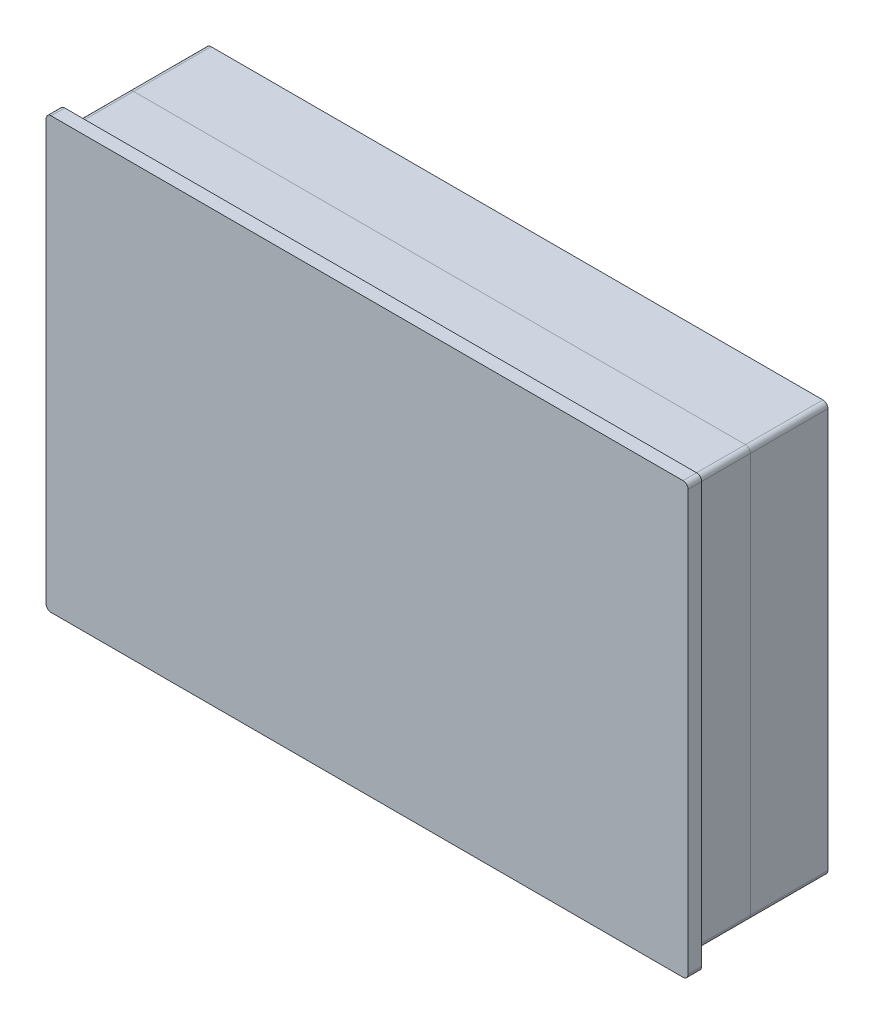
SolidWorks part; units mm, degrees
ref_plane "Front Plane" through (0, 0, 0) normal (0, 0, 1) x (1, 0, 0)
ref_plane "Top Plane" through (0, 0, 0) normal (0, 1, 0) x (1, 0, 0)
ref_plane "Right Plane" through (0, 0, 0) normal (1, 0, 0) x (0, 0, -1)
sketch "Sketch1" plane through (0, 0, 0) normal (0, 0, 1) x (1, 0, 0)
  line L1 (-140.9464, -80.3248) -> (-13.3464, -80.3248)
  line L2 (-140.9464, -80.3248) -> (-140.9464, -165.8248)
  line L3 (-140.9464, -165.8248) -> (-13.3464, -165.8248)
  line L4 (-13.3464, -80.3248) -> (-13.3464, -165.8248)
  line L5 (-140.9464, -80.3248) -> (-13.3464, -165.8248) construction
  line L6 (-140.9464, -165.8248) -> (-13.3464, -80.3248) construction
  point P0 (-77.1464, -123.0748)
  dimension "D1" = 127.6
  dimension "D2" = 85.5
extrude "Boss-Extrude1" add sketch "Sketch1" along normal blind 14.4
sketch "Sketch2" plane through (0, 0, 0) normal (0, 0, -1) x (-1, 0, 0)
  line L8 (15.3464, -82.3248) -> (15.3464, -163.8248)
  line L9 (15.3464, -163.8248) -> (138.9464, -163.8248)
  line L10 (138.9464, -163.8248) -> (138.9464, -82.3248)
  line L11 (138.9464, -82.3248) -> (15.3464, -82.3248)
  line L12 (15.3464, -82.3248) -> (15.3464, -163.8248)
  line L13 (15.3464, -163.8248) -> (138.9464, -163.8248)
  line L14 (138.9464, -163.8248) -> (138.9464, -82.3248)
  line L15 (138.9464, -82.3248) -> (15.3464, -82.3248)
  line L16 (13.3464, -80.3248) -> (13.3464, -165.8248)
  line L17 (13.3464, -165.8248) -> (140.9464, -165.8248)
  line L18 (140.9464, -165.8248) -> (140.9464, -80.3248)
  line L19 (140.9464, -80.3248) -> (13.3464, -80.3248)
  line L20 (13.3464, -80.3248) -> (13.3464, -165.8248)
  line L21 (13.3464, -165.8248) -> (140.9464, -165.8248)
  line L22 (140.9464, -165.8248) -> (140.9464, -80.3248)
  line L23 (140.9464, -80.3248) -> (13.3464, -80.3248)
  dimension "D1" = 2
  dimension "D2" = 0
extrude "Cut-Extrude1" cut sketch "Sketch2" against normal blind 11.7
sketch "Sketch3" plane through (0, 0, 0) normal (0, 0, -1) x (-1, 0, 0)
  line L4 (138.9464, -82.3248) -> (15.3464, -82.3248)
  line L5 (15.3464, -82.3248) -> (15.3464, -163.8248)
  line L6 (15.3464, -163.8248) -> (138.9464, -163.8248)
  line L7 (138.9464, -163.8248) -> (138.9464, -82.3248)
  line L8 (138.9464, -82.3248) -> (15.3464, -82.3248)
  line L9 (15.3464, -82.3248) -> (15.3464, -163.8248)
  line L10 (15.3464, -163.8248) -> (138.9464, -163.8248)
  line L11 (138.9464, -163.8248) -> (138.9464, -82.3248)
  dimension "D1" = 0
extrude "Boss-Extrude2" add sketch "Sketch3" along normal blind 15.4 separate body
fillet "Fillet1" radius 1 8 edges at (-13.3464, -80.3248, 13.05) (-13.3464, -165.8248, 13.05) (-140.9464, -165.8248, 13.05) (-140.9464, -80.3248, 13.05) (-138.9464, -163.8248, 5.85) (-138.9464, -82.3248, 5.85) (-15.3464, -82.3248, 5.85) (-15.3464, -163.8248, 5.85)
fillet "Fillet2" radius 1 4 edges at (-15.3464, -163.8248, -7.7) (-138.9464, -163.8248, -7.7) (-138.9464, -82.3248, -7.7) (-15.3464, -82.3248, -7.7)
